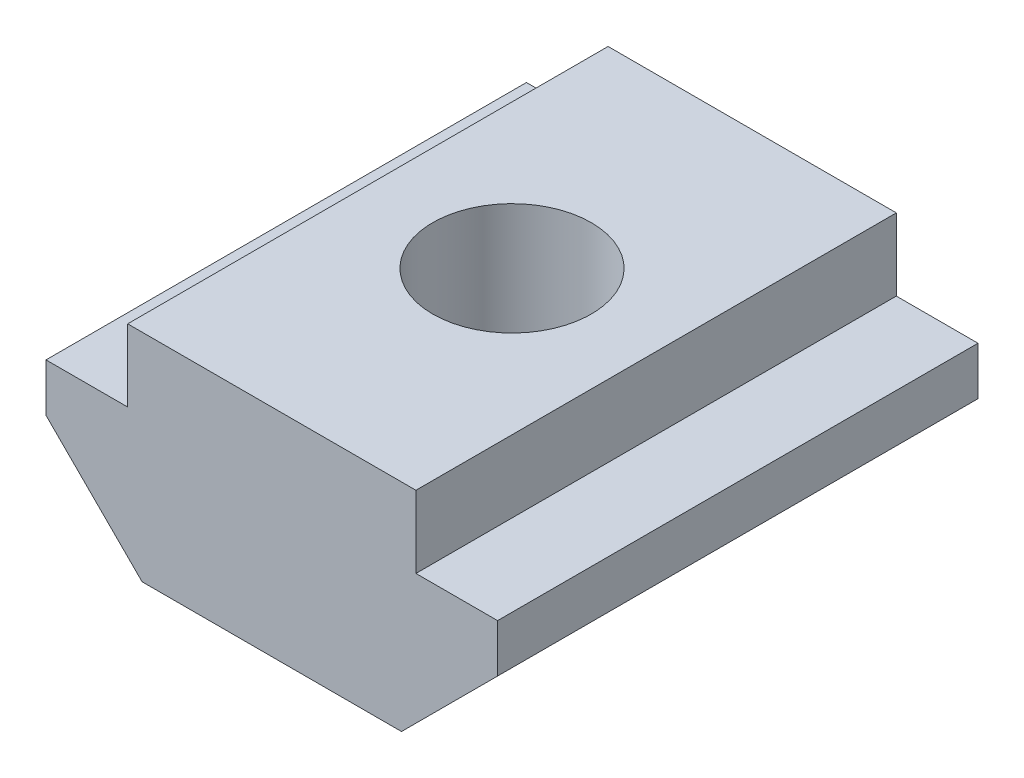
SolidWorks part; units mm, degrees
ref_plane "前视基准面" through (0, 0, 0) normal (0, 0, 1) x (1, 0, 0)
ref_plane "上视基准面" through (0, 0, 0) normal (0, 1, 0) x (1, 0, 0)
ref_plane "右视基准面" through (0, 0, 0) normal (1, 0, 0) x (0, 0, -1)
sketch "草图1" plane through (0, 0, 0) normal (0, 0, 1) x (1, 0, 0)
  line L0 (0, 0) -> (1.7, 0)
  line L1 (1.7, 0) -> (1.7, 1.5)
  line L2 (1.7, 1.5) -> (7.7, 1.5)
  line L3 (7.7, 1.5) -> (7.7, 0)
  line L4 (7.7, 0) -> (9.4, 0)
  line L5 (9.4, 0) -> (9.4, -1)
  line L6 (9.4, -1) -> (7.4, -3)
  line L7 (7.4, -3) -> (2, -3)
  line L8 (2, -3) -> (0, -1)
  line L9 (0, -1) -> (0, 0)
  dimension "D1" = 3
  dimension "D2" = 2
  dimension "D3" = 2
  dimension "D4" = 1.7
  dimension "D5" = 6
  dimension "D6" = 4.5
  dimension "D7" = 5.4
  dimension "D8" = 9.4
  dimension "D9" = 2
extrude "拉伸1" add sketch "草图1" along normal blind 10
hole_wizard "M4 螺纹孔1" positions "3D草图1" profile "草图2" tap size "M4" standard "GB" end condition through all
sketch3d "3D草图1"
  line L0 (7.7, 1.5, 10) -> (7.7, 1.5, 0) construction
  point P0 (4.7, 1.5, 5)
  dimension "D1" = 3
  dimension "D2" = 5
sketch "草图2" plane through (4.7, 1.5, 5) normal (1, 0, 0) x (0, 0, 1)
  line L0 (0, 0) -> (0, 4.5)
  line L1 (0, 4.5) -> (1.65, 4.5)
  line L2 (1.65, 4.5) -> (1.65, 0)
  line L5 (1.65, 0) -> (0, 0)
  line L11 (0, -6.35) -> (0, 107.95) construction
  dimension "籵謂蹟恇謂郰芛眻噤" = 3.3
  dimension "籵謂蹟恇謂郰芛旮僅" = 4.5
cosmetic thread "孔螺蚊线1" parameters "D2"=4
